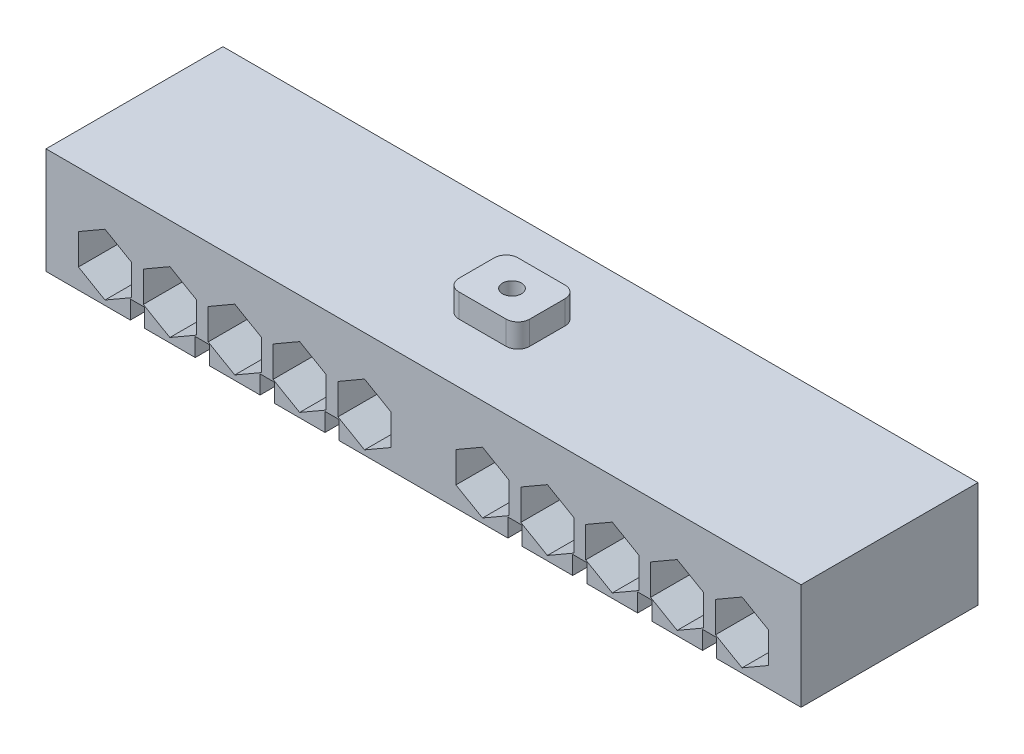
SolidWorks part; units mm, degrees
ref_plane "Front Plane" through (0, 0, 0) normal (0, 0, 1) x (1, 0, 0)
ref_plane "Top Plane" through (0, 0, 0) normal (0, 1, 0) x (1, 0, 0)
ref_plane "Right Plane" through (0, 0, 0) normal (1, 0, 0) x (0, 0, -1)
sketch "Sketch1" plane through (0, 0, 0) normal (0, 1, 0) x (1, 0, 0)
  line L1 (-32, 7.5) -> (32, 7.5)
  line L2 (-32, 7.5) -> (-32, -7.5)
  line L3 (-32, -7.5) -> (32, -7.5)
  line L4 (32, 7.5) -> (32, -7.5)
  line L5 (-32, 7.5) -> (32, -7.5) construction
  line L6 (-32, -7.5) -> (32, 7.5) construction
  point P0 (0, 0)
  dimension "D1" = 64
  dimension "D2" = 15
extrude "Boss-Extrude1" add sketch "Sketch1" along normal blind 9
sketch "Sketch2" plane through (0, 0, 7.5) normal (0, 0, 1) x (1, 0, 0)
  line L0 (0, 9) -> (0, 0) construction
  line L1 (-32, 4.5) -> (32, 4.5) construction
  line L2 (10.5, 0.4) -> (12.7517, 1.7)
  line L3 (5, 0.4) -> (7.2517, 1.7)
  line L4 (-32, 0) -> (32, 0)
  line L5 (32, 0) -> (32, 9)
  line L6 (32, 9) -> (-32, 9)
  line L7 (-32, 9) -> (-32, 0)
  line L8 (-32, 0) -> (32, 0)
  line L9 (32, 0) -> (32, 9)
  line L10 (32, 9) -> (-32, 9)
  line L11 (-32, 9) -> (-32, 0)
  line L12 (7.2517, 1.7) -> (7.2517, 4.3)
  line L13 (7.2517, 4.3) -> (5, 5.6)
  line L14 (5, 5.6) -> (2.7483, 4.3)
  line L15 (2.7483, 4.3) -> (2.7483, 1.7)
  line L16 (2.7483, 1.7) -> (5, 0.4)
  line L17 (12.7517, 1.7) -> (12.7517, 4.3)
  line L18 (12.7517, 4.3) -> (10.5, 5.6)
  line L19 (10.5, 5.6) -> (8.2483, 4.3)
  line L20 (8.2483, 4.3) -> (8.2483, 1.7)
  line L21 (8.2483, 1.7) -> (10.5, 0.4)
  line L22 (16, 0.4) -> (18.2517, 1.7)
  line L23 (18.2517, 1.7) -> (18.2517, 4.3)
  line L24 (18.2517, 4.3) -> (16, 5.6)
  line L25 (16, 5.6) -> (13.7483, 4.3)
  line L26 (13.7483, 4.3) -> (13.7483, 1.7)
  line L27 (13.7483, 1.7) -> (16, 0.4)
  line L28 (21.5, 0.4) -> (23.7517, 1.7)
  line L29 (23.7517, 1.7) -> (23.7517, 4.3)
  line L30 (23.7517, 4.3) -> (21.5, 5.6)
  line L31 (21.5, 5.6) -> (19.2483, 4.3)
  line L32 (19.2483, 4.3) -> (19.2483, 1.7)
  line L33 (19.2483, 1.7) -> (21.5, 0.4)
  line L34 (27, 0.4) -> (29.2517, 1.7)
  line L35 (29.2517, 1.7) -> (29.2517, 4.3)
  line L36 (29.2517, 4.3) -> (27, 5.6)
  line L37 (27, 5.6) -> (24.7483, 4.3)
  line L38 (24.7483, 4.3) -> (24.7483, 1.7)
  line L39 (24.7483, 1.7) -> (27, 0.4)
  circle A0 centre (5, 3) radius 2.2517 construction
  dimension "D2" = 0.4
  dimension "D3" = 2.6
  dimension "D4" = 5
  dimension "D1" = 0
  dimension "D5" = 5
extrude "Cut-Extrude1" cut sketch "Sketch2" against normal blind 10 contours L20 L21 L2 L17 L18 L19 | L26 L27 L22 L23 L24 L25 | L32 L33 L28 L29 L30 L31 | L38 L39 L34 L35 L36 L37 | L15 L16 L3 L12 L13 L14
mirror "Mirror1" about plane through (0, 0, 0) normal (1, 0, 0) of "Cut-Extrude1"
sketch "Sketch3" plane through (0, 0, -7.5) normal (0, 0, -1) x (-1, 0, 0)
  line L0 (-32, 4.5) -> (32, 4.5) construction
  line L1 (0, 9) -> (0, 0) construction
  line L4 (-32, 0) -> (32, 0)
  line L5 (32, 0) -> (32, 9)
  line L6 (32, 9) -> (-32, 9)
  line L7 (-32, 9) -> (-32, 0)
  line L8 (-32, 0) -> (32, 0)
  line L9 (32, 0) -> (32, 9)
  line L10 (32, 9) -> (-32, 9)
  line L11 (-32, 9) -> (-32, 0)
  circle A0 centre (-5, 3) radius 2.5
  circle A1 centre (-10.5, 3) radius 2.5
  circle A2 centre (-16, 3) radius 2.5
  circle A3 centre (-21.5, 3) radius 2.5
  circle A4 centre (-27, 3) radius 2.5
  dimension "D2" = 5
  dimension "D3" = 3
  dimension "D4" = 5
  dimension "D1" = 0
  dimension "D5" = 5
extrude "Cut-Extrude2" cut sketch "Sketch3" against normal blind 3 contours A4 | A3 | A1 | A2 | A0
mirror "Mirror2" about plane through (0, 0, 0) normal (1, 0, 0) of "Cut-Extrude2"
sketch "Sketch4" plane through (0, 9, 0) normal (0, 1, 0) x (1, 0, 0)
  line L1 (-3, 2.5) -> (3, 2.5)
  line L2 (-3, 2.5) -> (-3, -2.5)
  line L3 (-3, -2.5) -> (3, -2.5)
  line L4 (32, -7.5) -> (32, 7.5)
  line L5 (32, 7.5) -> (-32, 7.5)
  line L6 (-32, 7.5) -> (-32, -7.5)
  line L7 (-32, -7.5) -> (32, -7.5)
  line L8 (32, -7.5) -> (32, 7.5)
  line L9 (32, 7.5) -> (-32, 7.5)
  line L10 (-32, 7.5) -> (-32, -7.5)
  line L11 (-32, -7.5) -> (32, -7.5)
  line L12 (3, 2.5) -> (3, -2.5)
  line L13 (-3, 2.5) -> (3, -2.5) construction
  line L14 (-3, -2.5) -> (3, 2.5) construction
  point P2 (0, 0)
  dimension "D2" = 5
  dimension "D3" = 6
  dimension "D1" = 0
extrude "Boss-Extrude2" add sketch "Sketch4" along normal blind 2 contours L2 L1 L12 L3
fillet "Fillet1" radius 1 4 edges at (-3, 10, -2.5) (3, 10, -2.5) (-3, 10, 2.5) (3, 10, 2.5)
sketch "Sketch5" plane through (0, 11, 0) normal (0, 1, 0) x (1, 0, 0)
  line L32 (2, 2.5) -> (-2, 2.5)
  line L33 (2, 2.5) -> (-2, 2.5)
  line L34 (-3, 1.5) -> (-3, -1.5)
  line L35 (-3, 1.5) -> (-3, -1.5)
  line L36 (-2, -2.5) -> (2, -2.5)
  line L37 (-2, -2.5) -> (2, -2.5)
  line L38 (3, -1.5) -> (3, 1.5)
  line L39 (3, -1.5) -> (3, 1.5)
  arc A4 (-2, 2.5) -> (-3, 1.5) centre (-2, 1.5) ccw
  arc A5 (-2, 2.5) -> (-3, 1.5) centre (-2, 1.5) ccw
  arc A6 (-3, -1.5) -> (-2, -2.5) centre (-2, -1.5) ccw
  arc A7 (-3, -1.5) -> (-2, -2.5) centre (-2, -1.5) ccw
  arc A8 (2, -2.5) -> (3, -1.5) centre (2, -1.5) ccw
  arc A9 (2, -2.5) -> (3, -1.5) centre (2, -1.5) ccw
  arc A10 (3, 1.5) -> (2, 2.5) centre (2, 1.5) ccw
  arc A11 (3, 1.5) -> (2, 2.5) centre (2, 1.5) ccw
  point P2 (0, 0)
  point P14 (0, 0)
  dimension "D1" = 0
hole_wizard "M2 Tapped Hole2" positions "3DSketch1" profile "Sketch7" tap size "M2" standard "ISO"
sketch3d "3DSketch1"
  point P0 (0, 0, 0)
  point P3 (0, 0, 0)
  point P5 (0, 0, 0)
  point P7 (0, 0, 0)
  point P9 (0, 0, 0)
  point P11 (0, 0, 0)
  point P13 (0, 11, 0)
sketch "Sketch7" plane through (0, 11, 0) normal (1, 0, 0) x (0, 0, 1)
  line L0 (0, 0) -> (0, 6)
  line L1 (0, 6) -> (0.8, 5.5193)
  line L2 (0.8, 5.5193) -> (0.8, 0)
  line L5 (0.8, 0) -> (0, 0)
  line L10 (0, 6) -> (-0.8, 5.5193) construction
  line L11 (0, -6.35) -> (0, 107.95) construction
  dimension "Tap Drill Dia." = 1.6
  dimension "Tap Drill Depth" = 6
  dimension "Drill Angle" = 118
cosmetic thread "Hole Thread13" parameters "D1"=4, "D2"=2
sketch "Sketch8" plane through (0, 0, 7.5) normal (0, 0, 1) x (1, 0, 0)
  line L0 (7.2517, 0) -> (7.2517, 1.7)
  line L1 (7.2517, 1.7) -> (8.2483, 1.7)
  line L2 (8.2483, 1.7) -> (8.2483, 0)
  line L3 (8.2483, 0) -> (7.2517, 0)
  line L4 (-32, 0) -> (32, 0)
  line L5 (32, 0) -> (32, 9)
  line L6 (32, 9) -> (-32, 9)
  line L7 (-32, 9) -> (-32, 0)
  line L8 (-32, 0) -> (32, 0)
  line L9 (32, 0) -> (32, 9)
  line L10 (32, 9) -> (-32, 9)
  line L11 (-32, 9) -> (-32, 0)
  line L12 (13.7483, 0) -> (12.7517, 0)
  line L13 (12.7517, 0) -> (12.7517, 1.7)
  line L14 (12.7517, 1.7) -> (13.7483, 1.7)
  line L15 (13.7483, 1.7) -> (13.7483, 0)
  line L16 (19.2483, 0) -> (18.2517, 0)
  line L17 (18.2517, 0) -> (18.2517, 1.7)
  line L18 (18.2517, 1.7) -> (19.2483, 1.7)
  line L19 (19.2483, 1.7) -> (19.2483, 0)
  line L20 (24.7483, 0) -> (23.7517, 0)
  line L21 (23.7517, 0) -> (23.7517, 1.7)
  line L22 (23.7517, 1.7) -> (24.7483, 1.7)
  line L23 (24.7483, 1.7) -> (24.7483, 0)
  dimension "D1" = 0
  dimension "D2" = 4
sketch "Sketch9" plane through (0, 0, 0) normal (0, -1, 0) x (1, 0, 0)
  line L2 (8.2483, 7.5) -> (7.2517, 7.5) construction
  line L23 (7.1488, 7.5) -> (8.3512, 7.5)
  line L24 (-32, 7.5) -> (32, 7.5) construction
  line L25 (32, 7.5) -> (-32, 7.5) construction
  line L26 (7.1488, 7.5) -> (7.1488, -7.5)
  line L27 (32, -7.5) -> (-32, -7.5) construction
  line L28 (7.1488, -7.5) -> (8.3512, -7.5)
  line L29 (8.3512, -7.5) -> (8.3512, 7.5)
  line L30 (13.8512, -7.5) -> (13.8512, 7.5)
  line L31 (12.6488, 7.5) -> (13.8512, 7.5)
  line L32 (12.6488, 7.5) -> (12.6488, -7.5)
  line L33 (12.6488, -7.5) -> (13.8512, -7.5)
  line L34 (19.3512, -7.5) -> (19.3512, 7.5)
  line L35 (18.1488, 7.5) -> (19.3512, 7.5)
  line L36 (18.1488, 7.5) -> (18.1488, -7.5)
  line L37 (18.1488, -7.5) -> (19.3512, -7.5)
  line L38 (24.8512, -7.5) -> (24.8512, 7.5)
  line L39 (23.6488, 7.5) -> (24.8512, 7.5)
  line L40 (23.6488, 7.5) -> (23.6488, -7.5)
  line L41 (23.6488, -7.5) -> (24.8512, -7.5)
  point P0 (7.75, 7.5)
  point P8 (7.75, 7.5)
  dimension "D1" = 4
extrude "Cut-Extrude3" cut sketch "Sketch9" against normal blind 1.55
mirror "Mirror3" about plane through (0, 0, 0) normal (1, 0, 0) of "Cut-Extrude3"
